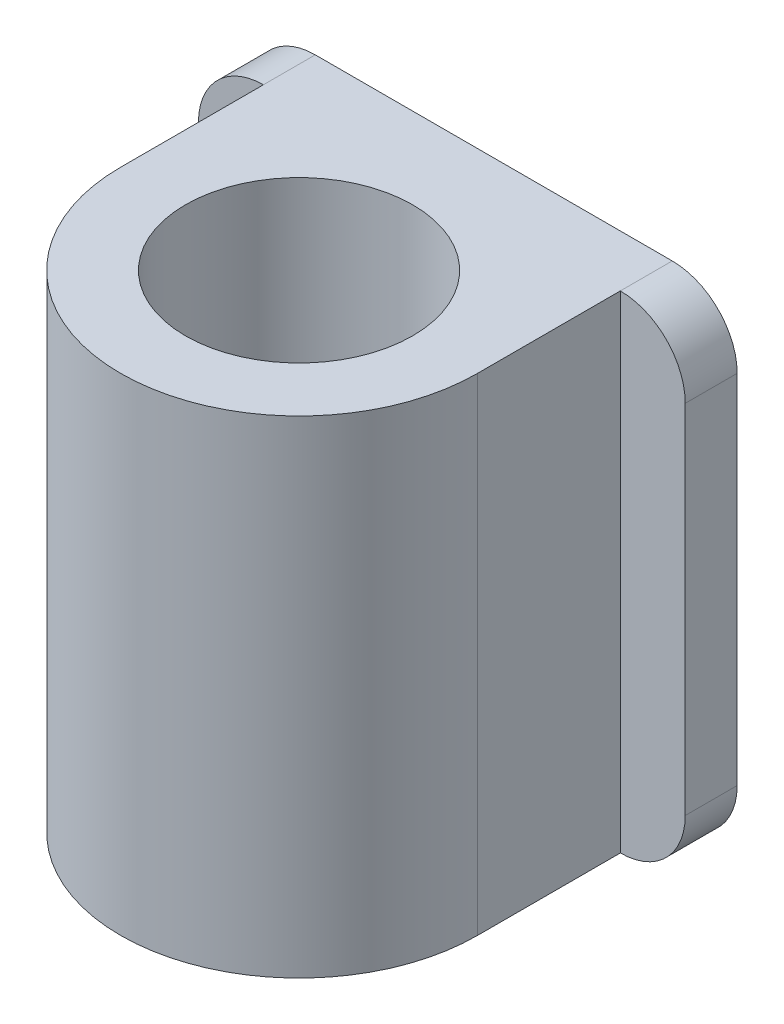
SolidWorks part; units mm, degrees
ref_plane "Front Plane" through (0, 0, 0) normal (0, 0, 1) x (1, 0, 0)
ref_plane "Top Plane" through (0, 0, 0) normal (0, 1, 0) x (1, 0, 0)
ref_plane "Right Plane" through (0, 0, 0) normal (1, 0, 0) x (0, 0, -1)
sketch "Sketch1" plane through (0, 0, 0) normal (0, 0, 1) x (1, 0, 0)
  line L1 (-37.5, -37.5) -> (37.5, -37.5)
  line L2 (-37.5, -37.5) -> (-37.5, 37.5)
  line L3 (-37.5, 37.5) -> (37.5, 37.5)
  line L4 (37.5, -37.5) -> (37.5, 37.5)
  line L5 (-37.5, -37.5) -> (37.5, 37.5) construction
  line L6 (-37.5, 37.5) -> (37.5, -37.5) construction
  point P0 (0, 0)
  dimension "D1" = 75
  dimension "D2" = 75
extrude "Boss-Extrude1" add sketch "Sketch1" along normal blind 8
fillet "Fillet1" radius 10 4 edges at (37.5, -37.5, 4) (-37.5, -37.5, 4) (37.5, 37.5, 4) (-37.5, 37.5, 4)
sketch "Sketch2" plane through (0, 0, 0) normal (0, 1, 0) x (1, 0, 0)
  line L0 (-27.5, -8) -> (-27.5, -30)
  line L1 (27.5, -30) -> (27.5, -8)
  line L2 (27.5, -8) -> (-27.5, -8)
  circle A0 centre (0, -30) radius 17.5
  arc A1 (-27.5, -30) -> (27.5, -30) centre (0, -30) ccw
  dimension "D1" = 35
  dimension "D2" = 30
extrude "Boss-Extrude2" add sketch "Sketch2" along normal mid plane 75
sketch "Sketch3" plane through (0, 37.5, 0) normal (0, 1, 0) x (1, 0, 0)
  circle A2 centre (0, -30) radius 17
  circle A3 centre (0, -30) radius 17
  dimension "D1" = 0.5
extrude "Boss-Extrude3" add sketch "Sketch3" against normal blind 200 separate body
sketch "Sketch4" plane through (0, -37.5, 0) normal (0, -1, 0) x (1, 0, 0)
  circle A1 centre (0, 30) radius 17
  circle A2 centre (0, 30) radius 17
  circle A4 centre (0, 30) radius 22
  circle A5 centre (0, 30) radius 22
  dimension "D1" = 0
  dimension "D2" = 5
extrude "Boss-Extrude4" add sketch "Sketch4" along normal blind 10
sketch "Sketch5" plane through (0, -162.5, 0) normal (0, -1, 0) x (1, 0, 0)
  line L0 (-8, 15) -> (-8, 5)
  line L1 (-8, 5) -> (-12.5, 5)
  line L2 (-12.5, 5) -> (-25, 17.5)
  line L3 (-25, 17.5) -> (-25, 82)
  line L4 (0, 0) -> (0, 57.5) construction
  line L5 (-25, 82) -> (0, 82)
  line L6 (0, 82) -> (0, 47)
  arc A0 (27.5, 30) -> (-27.5, 30) centre (0, 30) ccw construction
  circle A1 centre (0, 30) radius 17
  arc A2 (0, 47) -> (-8, 15) centre (0, 30) ccw
  dimension "D2" = 8
  dimension "D3" = 10
  dimension "D4" = 25
  dimension "D5" = 45
  dimension "D6" = 12.5
  dimension "D7" = 35
  dimension "D1" = 0
extrude "Boss-Extrude5" add sketch "Sketch5" against normal blind 50 separate body
mirror "Mirror1" about plane through (0, -112.5, 82) normal (1, 0, 0) of bodies 105
sketch "Sketch6" plane through (0, 0, 82) normal (0, 0, 1) x (1, 0, 0)
  line L0 (-25, -112.5) -> (25, -162.5) construction
  circle A0 centre (0, -137.5) radius 17.5
  dimension "D1" = 35
extrude "Cut-Extrude1" cut sketch "Sketch6" against normal blind 25
sketch "Sketch7" plane through (0, 0, 57) normal (0, 0, 1) x (1, 0, 0)
  circle A1 centre (0, -137.5) radius 17.5
  circle A2 centre (0, -137.5) radius 17.5
  dimension "D1" = 0
extrude "Boss-Extrude6" add sketch "Sketch7" along normal blind 100 separate body
sketch "Sketch8" plane through (25, 0, 0) normal (1, 0, 0) x (0, 0, -1)
  line L0 (-30, -47.5) -> (-30, -112.5) construction
  line L1 (-47, -47.5) -> (-13, -47.5) construction
  line L2 (-82, -112.5) -> (-17.5, -112.5) construction
  line L3 (-30, -112.5) -> (-30, -162.5) construction
  line L4 (-82, -162.5) -> (-17.5, -162.5) construction
  circle A0 centre (-30, -137.5) radius 5.5
  dimension "D1" = 11
extrude "Cut-Extrude2" cut sketch "Sketch8" against normal through all both and the other way through all
sketch "Sketch10" plane through (0, -162.5, 0) normal (0, -1, 0) x (1, 0, 0)
  circle A4 centre (0, 30) radius 14
  circle A5 centre (0, 30) radius 14
  dimension "D1" = 3
extrude "Cut-Extrude3" cut sketch "Sketch10" against normal through all both
chamfer "Chamfer1" distance 5 angle 45 1 edges at (25, -137.5, 24.5)
sketch "Sketch11" plane through (-25, 0, 0) normal (-1, 0, 0) x (0, 0, 1)
  line L1 (39, -142.6962) -> (39, -132.3038)
  line L2 (39, -132.3038) -> (30, -127.1077)
  line L3 (30, -127.1077) -> (21, -132.3038)
  line L4 (21, -132.3038) -> (21, -142.6962)
  line L5 (21, -142.6962) -> (30, -147.8923)
  line L6 (30, -147.8923) -> (39, -142.6962)
  circle A0 centre (30, -137.5) radius 9 construction
  dimension "D1" = 18
extrude "Cut-Extrude4" cut sketch "Sketch11" against normal blind 12
fillet "Fillet3" radius 3 6 edges at (-12.5, -137.5, 5) (12.5, -137.5, 5) (8, -137.5, 5) (-8, -137.5, 5) (25, -137.5, 17.5) (-25, -137.5, 17.5)
fillet "Fillet2" radius 3 28 edges at (12.4054, -162.5, 5.2284) (-12.4054, -162.5, 5.2284) (-11.1287, -112.5, 5) (-8, -112.5, 11.5) (18.75, -112.5, 11.25) (11.1287, -112.5, 5) (8, -112.5, 11.5) (-24.7716, -112.5, 17.5946) (24.7716, -112.5, 17.5946) (-8.8787, -112.5, 5.8787) (8.8787, -112.5, 5.8787) (12.4054, -112.5, 5.2284) (-12.4054, -112.5, 5.2284) (-25, -112.5, 50.3713) (25, -162.5, 50.3713) (25, -112.5, 50.3713) (-25, -162.5, 50.3713) (-18.75, -162.5, 11.25) (-18.75, -112.5, 11.25) (8, -162.5, 11.5) (11.1287, -162.5, 5) (18.75, -162.5, 11.25) (-11.1287, -162.5, 5) (-8, -162.5, 11.5) (-24.7716, -162.5, 17.5946) (24.7716, -162.5, 17.5946) (-8.8787, -162.5, 5.8787) (8.8787, -162.5, 5.8787)
delete or keep bodies "Body-Delete/Keep 1" type delete bodies bodies 114 115 108
